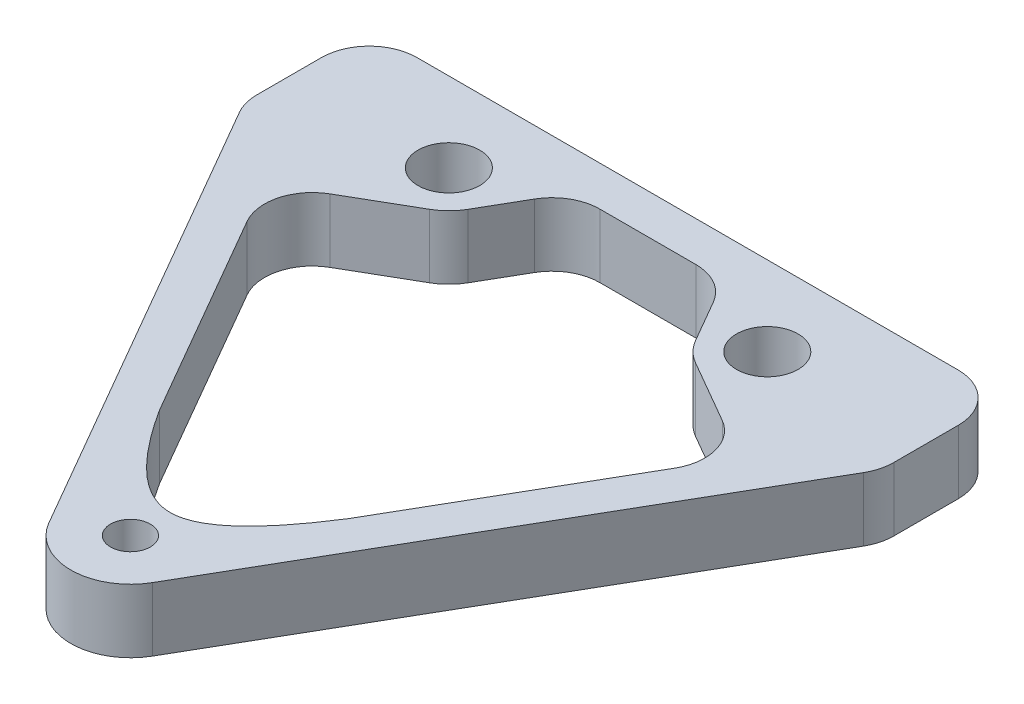
SolidWorks part; units mm, degrees
material "3D Printer - Undefined Plastic"
ref_plane "Front Plane" through (0, 0, 0) normal (0, 0, 1) x (1, 0, 0)
ref_plane "Top Plane" through (0, 0, 0) normal (0, 1, 0) x (1, 0, 0)
ref_plane "Right Plane" through (0, 0, 0) normal (1, 0, 0) x (0, 0, -1)
sketch "Sketch1" plane through (0, 0, 0) normal (0, 1, 0) x (1, 0, 0)
  line L0 (-25.4, 0) -> (25.4, 0)
  line L5 (25.4, 0) -> (25.4, -9.9809)
  line L6 (25.4, -9.9809) -> (4.1244, -46.8312)
  line L7 (0, 0) -> (0, -44.45) construction
  line L8 (-25.4, -9.9809) -> (-4.1244, -46.8312)
  line L9 (-25.4, 0) -> (-25.4, -9.9809)
  line L10 (-25.4, -6.35) -> (25.4, -6.35)
  line L11 (-25.4, -9.9809) -> (25.4, -9.9809) construction
  arc A0 (-4.1244, -46.8312) -> (4.1244, -46.8312) centre (0, -44.45) ccw
  arc A1 (0, -39.6875) -> (-4.1244, -46.8312) centre (0, -44.45) ccw construction
  arc A2 (4.1244, -46.8312) -> (0, -39.6875) centre (0, -44.45) ccw construction
  point P3 (0, 0)
  dimension "D3" = 9.525
  dimension "D1" = 50.8
  dimension "D2" = 44.45
  dimension "D4" = 6.35
  dimension "D5" = 60
extrude "Boss-Extrude1" add sketch "Sketch1" along normal blind 5.08 contours L8 A0 L6 L5 L10 L9 | L9 L10 L5 L0
hole_wizard "#10 (0.1935) Diameter Hole1" positions "Sketch12" profile "Sketch13" hole size "#10" standard "ANSI Inch" end condition through all
sketch "Sketch12" plane through (0, 5.08, 0) normal (0, 1, 0) x (1, 0, 0)
  line L0 (12.7, -6.35) -> (25.4, -6.35) construction
  line L1 (25.4, 0) -> (25.4, -9.9809) construction
  line L3 (-12.7, -6.35) -> (-25.4, -6.35) construction
  line L4 (-25.4, 0) -> (-25.4, -9.9809) construction
  line L6 (-25.4, 0) -> (25.4, 0) construction
  point P0 (-12.7, -6.35)
  point P2 (12.7, -6.35)
  point P17 (15.875, -4.36)
  dimension "D1" = 25.4
  dimension "D2" = 6.35
sketch "Sketch13" plane through (-12.7, 5.08, 6.35) normal (1, 0, 0) x (0, 0, 1)
  line L0 (0, 0) -> (0, 5.08)
  line L1 (0, 5.08) -> (2.4574, 5.08)
  line L2 (2.4574, 5.08) -> (2.4574, 0)
  line L5 (2.4574, 0) -> (0, 0)
  line L11 (0, -6.35) -> (0, 107.95) construction
  dimension "Thru Hole Dia." = 4.9149
  dimension "Thru Hole Depth" = 5.08
hole_wizard "1/8 (0.1250) Dowel Hole1" positions "Sketch14" profile "Sketch15" hole size "1/8" standard "ANSI Inch" end condition through all
sketch "Sketch14" plane through (0, 5.08, 0) normal (0, 1, 0) x (1, 0, 0)
  arc A0 (-4.1244, -46.8312) -> (4.1244, -46.8312) centre (0, -44.45) ccw construction
  point P0 (0, -44.45)
sketch "Sketch15" plane through (0, 5.08, 44.45) normal (1, 0, 0) x (0, 0, 1)
  line L0 (0, 0) -> (0, 5.08)
  line L1 (0, 5.08) -> (1.5875, 5.08)
  line L2 (1.5875, 5.08) -> (1.5875, 0)
  line L5 (1.5875, 0) -> (0, 0)
  line L11 (0, -6.35) -> (0, 107.95) construction
  dimension "Thru Hole Dia." = 3.175
  dimension "Thru Hole Depth" = 5.08
sketch "Sketch4" plane through (0, 5.08, 0) normal (0, 1, 0) x (1, 0, 0)
  line L1 (-9.0705, -8.4455) -> (-6.0276, -3.175)
  line L4 (6.0276, -3.175) -> (9.0705, -8.4455)
  line L9 (-19.3724, -3.175) -> (-16.3295, -8.4455)
  line L10 (19.3724, -3.175) -> (16.3295, -8.4455)
  line L11 (10.6045, -9.9795) -> (18.9521, -14.799)
  line L12 (-10.6045, -9.9795) -> (-18.9521, -14.799)
  line L14 (-10.0239, -30.362) -> (10.0239, -30.362) construction
  line L19 (-22.225, -9.1302) -> (-1.3748, -45.2438)
  line L20 (1.3748, -45.2437) -> (22.225, -9.1302)
  line L21 (22.225, -9.1302) -> (22.225, -3.175)
  line L22 (22.225, -3.175) -> (-22.225, -3.175)
  line L23 (-22.225, -3.175) -> (-22.225, -9.1302)
  line L24 (-22.225, -9.1302) -> (-1.3748, -45.2438)
  line L25 (1.3748, -45.2437) -> (22.225, -9.1302)
  line L26 (22.225, -9.1302) -> (22.225, -3.175)
  line L27 (22.225, -3.175) -> (-22.225, -3.175)
  line L28 (-22.225, -3.175) -> (-22.225, -9.1302)
  circle A2 centre (-12.7, -6.35) radius 4.191
  circle A3 centre (12.7, -6.35) radius 4.191
  circle A4 centre (0, -44.45) radius 1.5875 construction
  arc A5 (-1.3748, -45.2438) -> (1.3748, -45.2437) centre (0, -44.45) ccw
  arc A6 (-1.3748, -45.2438) -> (1.3748, -45.2437) centre (0, -44.45) ccw
  circle A7 centre (0, -44.45) radius 3.175 construction
  spline S0 degree 3 poles (11.7999, -27.187) (9.1515, -31.7741) (0, -50.7759) (-9.1515, -31.7741) (-11.7999, -27.187) knots 0 0 0 0 0.5 1 1 1 1
  dimension "D1" = 3.175
  dimension "D2" = 3.175
  dimension "D3" = 6.35
  dimension "D5" = 8.382
  dimension "D4" = 3.175
extrude "Cut-Extrude1" cut sketch "Sketch4" against normal through all contours S0 L25 L26 L27 L28 L24
fillet "Fillet1" radius 3.81 8 edges at (25.4, 2.54, 9.9809) (25.4, 2.54, 0) (-25.4, 2.54, 0) (-25.4, 2.54, 9.9809) (6.0276, 2.54, 3.175) (-6.0276, 2.54, 3.175) (-18.9521, 2.54, 14.799) (18.9521, 2.54, 14.799)
